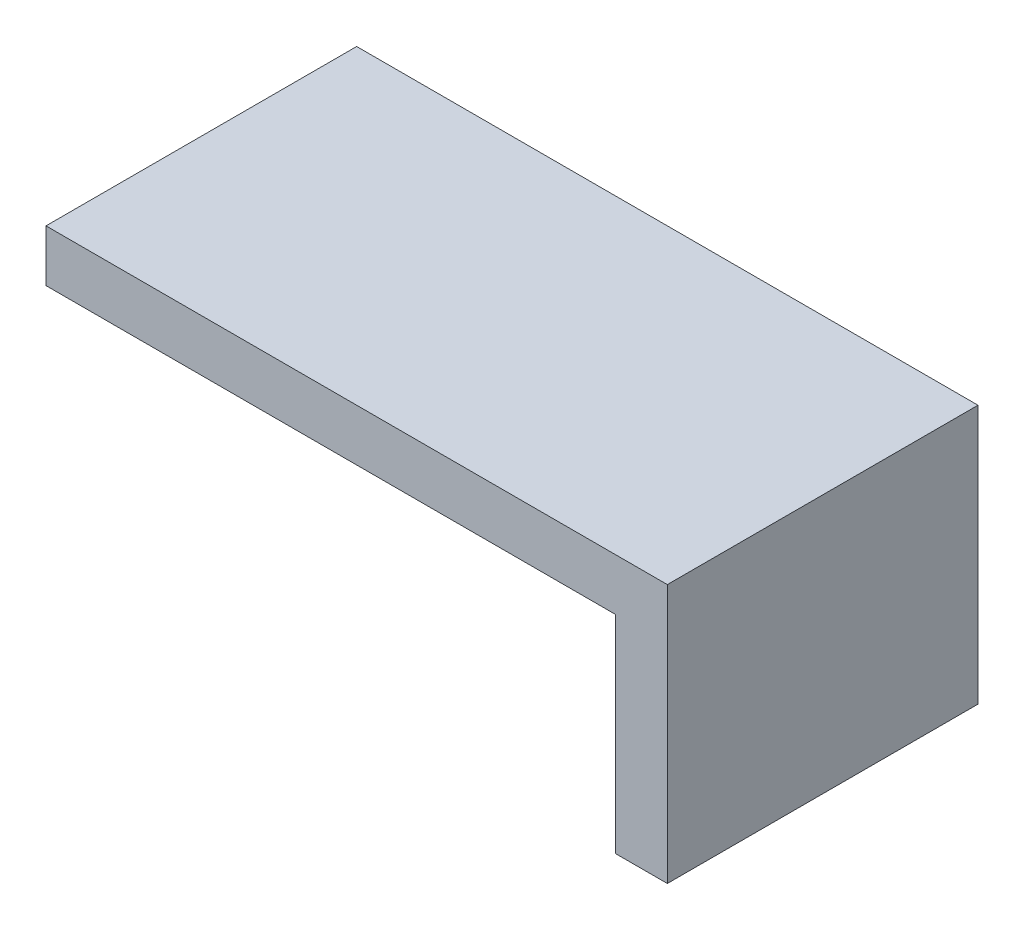
SolidWorks part; units mm, degrees
ref_plane "Front Plane" through (0, 0, 0) normal (0, 0, 1) x (1, 0, 0)
ref_plane "Top Plane" through (0, 0, 0) normal (0, 1, 0) x (1, 0, 0)
ref_plane "Right Plane" through (0, 0, 0) normal (1, 0, 0) x (0, 0, -1)
sketch "Sketch1" plane through (0, 0, 0) normal (0, 1, 0) x (1, 0, 0)
  line L1 (0, 0) -> (60, 0)
  line L2 (0, 0) -> (0, 30)
  line L3 (0, 30) -> (60, 30)
  line L4 (60, 0) -> (60, 30)
  dimension "D1" = 60
  dimension "D2" = 30
extrude "Boss-Extrude1" add sketch "Sketch1" along normal blind 5
sketch "Sketch2" plane through (0, 0, 0) normal (0, -1, 0) x (1, 0, 0)
  line L0 (60, -30) -> (0, -30) construction
  line L1 (60, 0) -> (55, 0)
  line L2 (60, 0) -> (60, -30)
  line L3 (60, -30) -> (55, -30)
  line L4 (55, 0) -> (55, -30)
  dimension "D1" = 5
extrude "Boss-Extrude2" add sketch "Sketch2" along normal blind 20
